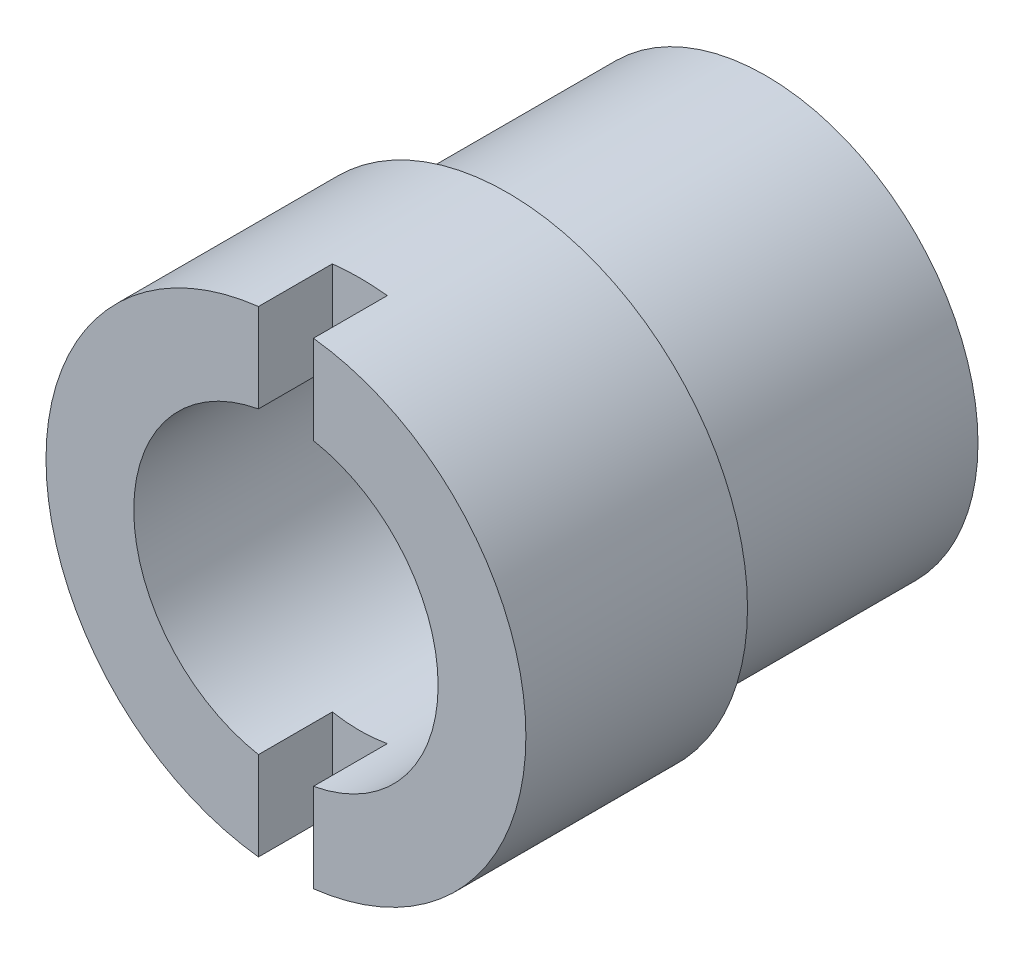
SolidWorks part; units mm, degrees
ref_plane "Front Plane" through (0, 0, 0) normal (0, 0, 1) x (1, 0, 0)
ref_plane "Top Plane" through (0, 0, 0) normal (0, 1, 0) x (1, 0, 0)
ref_plane "Right Plane" through (0, 0, 0) normal (1, 0, 0) x (0, 0, -1)
sketch "Sketch1" plane through (0, 0, 0) normal (0, 0, 1) x (1, 0, 0)
  circle A0 centre (0, 0) radius 10.3124
  circle A1 centre (0, 0) radius 6.5405
  dimension "D1" = 13.081
  dimension "D2" = 20.6248
extrude "Boss-Extrude1" add sketch "Sketch1" against normal blind 9.525
cosmetic thread "Cosmetic Thread1" parameters "D1"=9.525, "D2"=19.3802
sketch "Sketch2" plane through (0, 0, -9.525) normal (0, 0, -1) x (-1, 0, 0)
  circle A0 centre (0, 0) radius 6.5405 construction
  circle A1 centre (0, 0) radius 6.5405
  circle A2 centre (0, 0) radius 9.1186
extrude "Boss-Extrude2" add sketch "Sketch2" along normal blind 11.0998
sketch "Sketch3" plane through (0, 0, 0) normal (0, 1, 0) x (1, 0, 0)
  line L0 (-10.3124, 0) -> (10.3124, 0) construction
  line L1 (-1.1811, 0) -> (1.1811, 0)
  line L2 (-1.1811, 0) -> (-1.1811, 3.175)
  line L3 (-1.1811, 3.175) -> (1.1811, 3.175)
  line L4 (1.1811, 0) -> (1.1811, 3.175)
  dimension "D1" = 2.3622
  dimension "D2" = 3.175
extrude "Cut-Extrude1" cut sketch "Sketch3" against normal through all both and the other way through all
